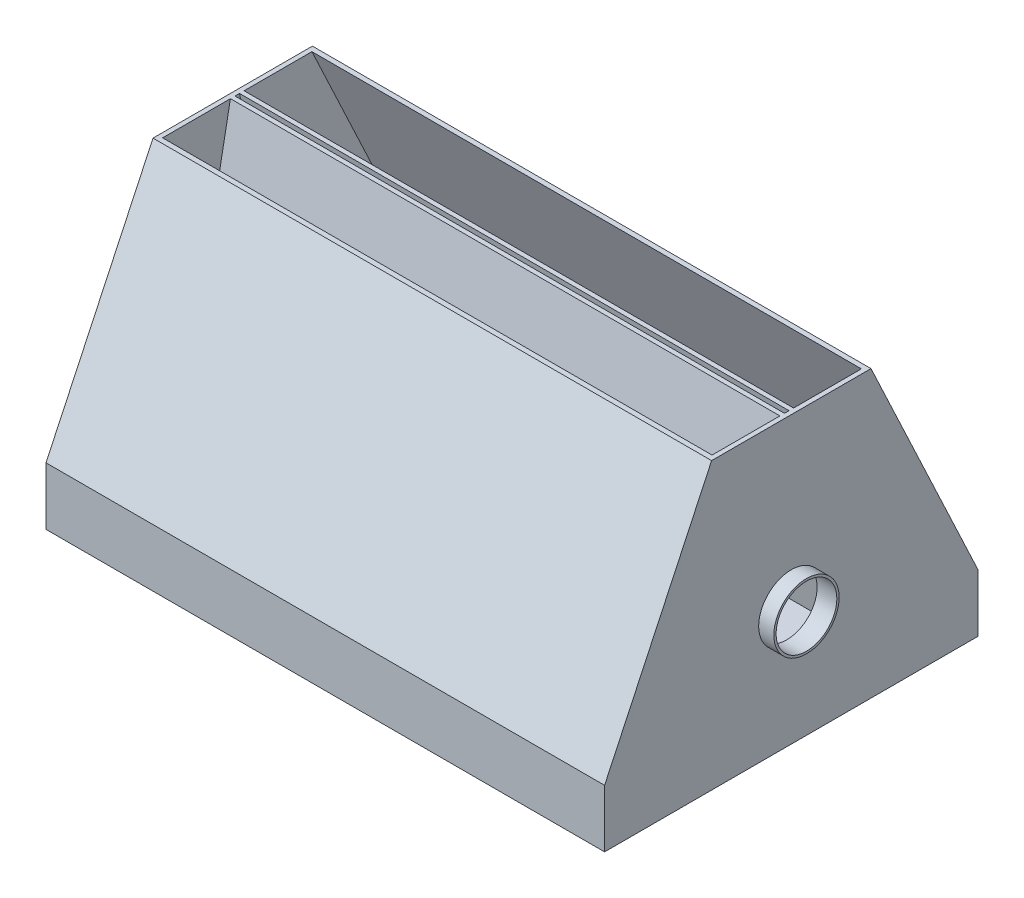
SolidWorks part; units mm, degrees
ref_plane "Front Plane" through (0, 0, 0) normal (0, 0, 1) x (1, 0, 0)
ref_plane "Top Plane" through (0, 0, 0) normal (0, 1, 0) x (1, 0, 0)
ref_plane "Right Plane" through (0, 0, 0) normal (1, 0, 0) x (0, 0, -1)
sketch "Sketch2" plane through (0, 0, 0) normal (1, 0, 0) x (0, 0, -1)
  line L21 (123, -50) -> (-123, -50)
  line L23 (-52.5, 100) -> (52.5, 100)
  line L28 (-52.5, 100) -> (-123, -50)
  line L29 (52.5, 100) -> (123, -50)
  point P0 (0, 0)
  point P2 (0, -50)
  point P8 (0, 100)
  dimension "D1" = 246
  dimension "D2" = 105
  dimension "D3" = 150
  dimension "D4" = 165.7415
extrude "Boss-Extrude1" add sketch "Sketch2" along normal blind 368
shell "Shell2" thickness 3
sketch "Sketch8" plane through (368, 0, 0) normal (1, 0, 0) x (0, 0, -1)
  line L0 (-123, -50) -> (123, -50) construction
  line L17 (-30, -35) -> (30, -35)
  line L25 (-123, -50) -> (123, -50)
  line L28 (52.5, 100) -> (-52.5, 100) construction
  line L29 (4.5, 100) -> (30, -35)
  line L31 (-4.5, 100) -> (-30, -35)
  line L32 (-4.5, 100) -> (-1.5, 100)
  line L33 (4.5, 100) -> (1.5, 100)
  line L34 (-1.5, 100) -> (-26.4333, -32)
  line L35 (1.5, 100) -> (26.4333, -32)
  line L37 (-26.4333, -32) -> (26.4333, -32)
  point P2 (0, -50)
  point P3 (0, -35)
  dimension "D2" = 3
  dimension "D3" = 48
  dimension "D1" = 3
  dimension "D6" = 3
  dimension "D7" = 60
  dimension "D8" = 15
extrude "Boss-Extrude3" add sketch "Sketch8" against normal through all
sketch "Sketch9" plane through (368, 0, 0) normal (1, 0, 0) x (0, 0, -1)
  line L0 (-123, -50) -> (123, -50) construction
  circle A1 centre (0, -10) radius 20
  point P4 (0, -50)
  dimension "D2" = 40
  dimension "D1" = 40
extrude "Cut-Extrude1" cut sketch "Sketch9" against normal up to next
sketch "Sketch10" plane through (368, 0, 0) normal (1, 0, 0) x (0, 0, -1)
  line L0 (-123, -50) -> (123, -50) construction
  circle A2 centre (0, -10) radius 20
  circle A3 centre (0, -10) radius 21.5
  dimension "D1" = 43
  dimension "D2" = 40
  dimension "D3" = 40
extrude "Boss-Extrude4" add sketch "Sketch10" along normal blind 10
sketch "Sketch11" plane through (0, -50, 0) normal (0, -1, 0) x (1, 0, 0)
  line L4 (3, 120) -> (3, -120)
  line L5 (3, -120) -> (365, -120)
  line L6 (365, -120) -> (365, 120)
  line L7 (365, 120) -> (3, 120)
  line L8 (0, 123) -> (0, -123)
  line L9 (0, -123) -> (368, -123)
  line L10 (368, -123) -> (368, 123)
  line L11 (0, -123) -> (368, -123)
  line L12 (0, 123) -> (0, -123)
  line L14 (368, -123) -> (368, 123)
  line L16 (0, -123) -> (368, -123) construction
  line L17 (368, 123) -> (0, 123) construction
  line L18 (368, 123) -> (0, 123)
  line L19 (368, 123) -> (0, 123)
  dimension "D1" = 0
  dimension "D2" = 3
extrude "Boss-Extrude5" add sketch "Sketch11" along normal blind 38
